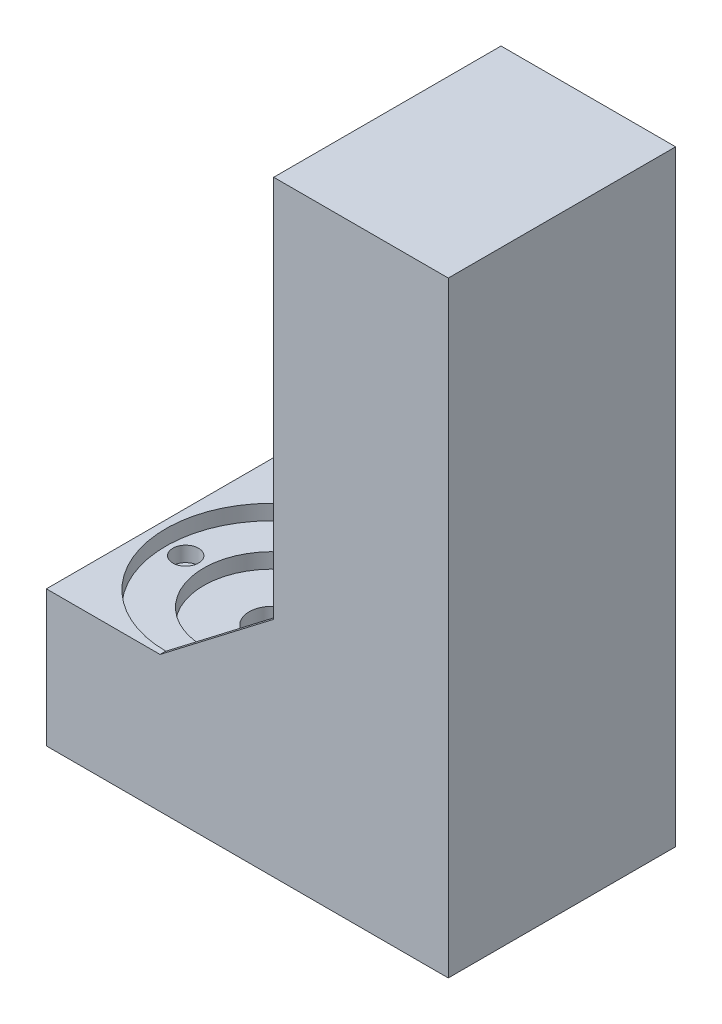
SolidWorks part; units mm, degrees
ref_plane "Front Plane" through (0, 0, 0) normal (0, 0, 1) x (1, 0, 0)
ref_plane "Top Plane" through (0, 0, 0) normal (0, 1, 0) x (1, 0, 0)
ref_plane "Right Plane" through (0, 0, 0) normal (1, 0, 0) x (0, 0, -1)
sketch "Sketch1" plane through (0, 0, 0) normal (0, 0, 1) x (1, 0, 0)
  line L1 (0, 0) -> (30, 0)
  line L2 (0, 0) -> (0, 17.96)
  line L3 (0, 17.96) -> (30, 17.96)
  line L4 (30, 0) -> (30, 17.96)
  line L5 (30, 0) -> (53.04, 0)
  line L6 (30, 0) -> (30, 80)
  line L7 (30, 80) -> (53.04, 80)
  line L8 (53.04, 0) -> (53.04, 80)
  dimension "D1" = 30
  dimension "D2" = 17.96
  dimension "D3" = 80
  dimension "D4" = 23.04
extrude "Boss-Extrude1" add sketch "Sketch1" along normal blind 30 contours L6 L5 L8 L7 | L2 L1 L4 L3
sketch "Sketch2" plane through (0, 17.96, 0) normal (0, 1, 0) x (1, 0, 0)
  line L0 (15, 0) -> (15, -30) construction
  line L1 (0, 0) -> (30, 0) construction
  line L2 (0, -30) -> (30, -30) construction
  line L3 (0, -15.2403) -> (26.6816, -15.2403) construction
  line L4 (0, -30) -> (0, 0) construction
  circle A0 centre (15, -15.2403) radius 14
  dimension "D1" = 28
extrude "Cut-Extrude1" cut sketch "Sketch2" against normal blind 2
sketch "Sketch3" plane through (0, 15.96, 0) normal (0, 1, 0) x (1, 0, 0)
  line L0 (15, 0) -> (15, -33.2933) construction
  line L1 (0, 0) -> (30, 0) construction
  line L2 (0, -15) -> (15, -15) construction
  line L3 (0, -30) -> (0, 0) construction
  line L4 (15, -15) -> (45.5379, -15) construction
  circle A0 centre (15, -3.4) radius 1.7
  circle A1 centre (26.6, -14.899) radius 1.7
  circle A2 centre (14.9973, -26.6) radius 1.7
  circle A3 centre (3.4, -15.0182) radius 1.7
  dimension "D1" = 3.4
  dimension "D2" = 23.2
  dimension "D3" = 23.2
extrude "Cut-Extrude2" cut sketch "Sketch3" against normal blind 2
sketch "Sketch4" plane through (0, 15.96, 0) normal (0, 1, 0) x (1, 0, 0)
  circle A0 centre (15, -15.2403) radius 9
  dimension "D1" = 18
extrude "Cut-Extrude3" cut sketch "Sketch4" against normal blind 2
sketch "Sketch5" plane through (0, 13.96, 0) normal (0, 1, 0) x (1, 0, 0)
  circle A0 centre (15, -15.2403) radius 3
  dimension "D1" = 6
extrude "Cut-Extrude6" cut sketch "Sketch5" against normal through all
sketch "Sketch6" plane through (30, 0, 0) normal (-1, 0, 0) x (0, 0, 1)
  line L0 (6.3397, 80) -> (6.3397, 17.96) construction
  line L1 (30, 80) -> (0, 80) construction
  line L2 (30, 17.96) -> (0, 17.96) construction
  line L3 (23.4072, 80) -> (23.4072, 2.1477) construction
  line L4 (4.6397, 75.3393) -> (4.6397, 30.2097)
  line L5 (8.0397, 30.2097) -> (8.0397, 75.3393)
  line L6 (21.7072, 75.3393) -> (21.7072, 30.2097)
  line L7 (25.1072, 30.2097) -> (25.1072, 75.3393)
  arc A7 (4.6397, 75.3393) -> (8.0397, 75.3393) centre (6.3397, 75.3393) cw
  arc A8 (4.6397, 30.2097) -> (8.0397, 30.2097) centre (6.3397, 30.2097) ccw
  arc A9 (21.7072, 30.2097) -> (25.1072, 30.2097) centre (23.4072, 30.2097) ccw
  arc A10 (25.1072, 75.3393) -> (21.7072, 75.3393) centre (23.4072, 75.3393) ccw
extrude "Cut-Extrude7" cut sketch "Sketch6" against normal blind 2
sketch "Sketch7" plane through (0, 0, 0) normal (0, 0, -1) x (-1, 0, 0)
  line L0 (-15, 17.96) -> (-30, 29.4758)
  line L1 (0, 17.96) -> (-30, 17.96) construction
  line L2 (-30, 17.96) -> (-30, 80) construction
  line L9 (-30, 80) -> (-53.04, 80)
  line L10 (-53.04, 80) -> (-53.04, 0)
  line L11 (-53.04, 0) -> (0, 0)
  line L12 (0, 0) -> (0, 17.96)
  line L13 (0, 17.96) -> (-30, 17.96)
  line L14 (-30, 17.96) -> (-30, 80)
  line L19 (-15, 17.96) -> (-30, 17.96)
  line L20 (-30, 17.96) -> (-30, 29.4758)
  dimension "D1" = 0
extrude "Boss-Extrude2" add sketch "Sketch7" against normal blind 1
sketch "Sketch8" plane through (0, 0, 30) normal (0, 0, 1) x (1, 0, 0)
  line L0 (15, 17.96) -> (30, 29.4758)
  line L1 (0, 17.96) -> (30, 17.96) construction
extrude "Extrude-Thin1" add sketch "Sketch8" against normal blind 0.7 thin
equation "\"L1\"= 30 * 10 ^ - 3"
equation "\"M1\"= 5.4"
equation "\"Sy\"= 4.52 * 10 ^ 7"
equation "\"Deflection\"= .00025"
equation "\"SF\"= 3.5"
equation "\"Modulus\"= 2.35 * 10 ^ 9"
equation "\"H1 stress\"= sqr ( ( 6 * \"M1\" * \"SF\" ) / ( \"Sy\" * \"L1\" ) )"
equation "\"H1 deflection\"= ( sqr ( ( 6 * \"M1\" * \"L1\" * \"SF\" ) / ( \"Modulus\" * \"Deflection\" ) ) ) * 1 / 3"
equation "\"M2\"= 11.4"
equation "\"H2 stress\"= sqr ( ( 6 * \"M2\" * \"SF\" ) / ( \"Sy\" * \"L1\" ) )"
equation "\"H2 deflection\"= ( sqr ( ( 6 * \"M2\" * \"L1\" * \"SF\" ) / ( \"Modulus\" * \"Deflection\" ) ) ) * 1 / 3"
